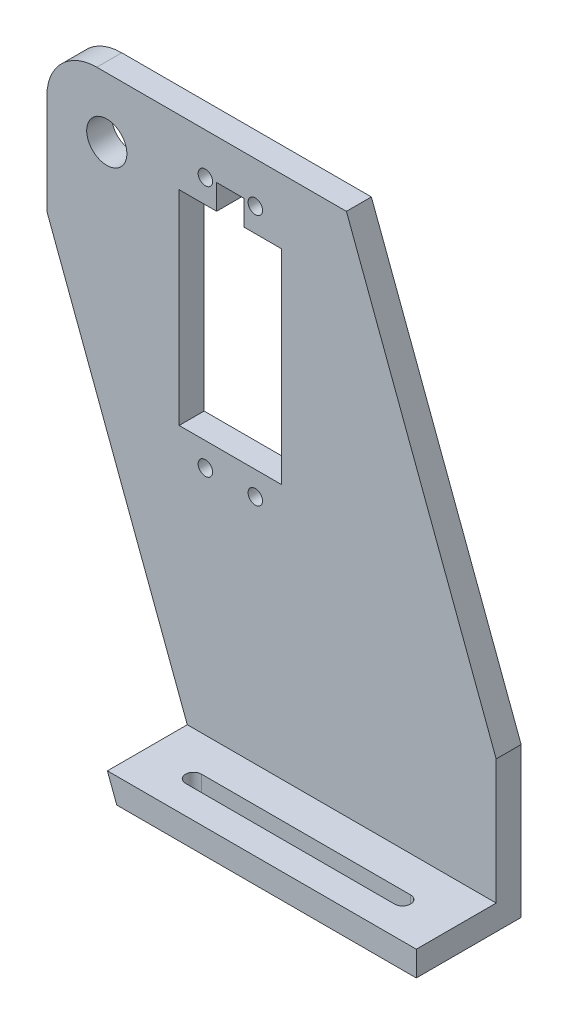
SolidWorks part; units mm, degrees
ref_plane "Front Plane" through (0, 0, 0) normal (0, 0, 1) x (1, 0, 0)
ref_plane "Top Plane" through (0, 0, 0) normal (0, 1, 0) x (1, 0, 0)
ref_plane "Right Plane" through (0, 0, 0) normal (1, 0, 0) x (0, 0, -1)
sketch "Sketch2" plane through (0, 0, 0) normal (0, 0, 1) x (1, 0, 0)
  line L1 (-45, 2.5) -> (45, 2.5)
  line L2 (-45, 2.5) -> (-45, -2.5)
  line L3 (-45, -2.5) -> (45, -2.5)
  line L4 (45, 2.5) -> (45, -2.5)
  line L5 (-45, 2.5) -> (45, -2.5) construction
  line L6 (-45, -2.5) -> (45, 2.5) construction
  point P0 (0, 0)
  dimension "D1" = 5
  dimension "D2" = 90
extrude "Boss-Extrude1" add sketch "Sketch2" along normal blind 21
sketch "Sketch3" plane through (0, 2.5, 0) normal (0, 1, 0) x (1, 0, 0)
  line L0 (45, -21) -> (45, 0) construction
  line L1 (-45, 0) -> (45, 0)
  line L2 (-45, 0) -> (-45, -5)
  line L3 (-45, -5) -> (45, -5)
  line L4 (45, 0) -> (45, -5)
  dimension "D1" = 5
extrude "Boss-Extrude2" add sketch "Sketch3" along normal blind 105
fillet "Fillet1" radius 10 1 edges at (-45, 107.5, 2.5)
sketch "Sketch4" plane through (0, 0, 5) normal (0, 0, 1) x (1, 0, 0)
  line L0 (-35, 107.5) -> (45, 107.5) construction
  line L1 (-45, 97.5) -> (-45, 2.5) construction
  circle A0 centre (-33, 95.5) radius 4.025
  dimension "D1" = 8.05
  dimension "D2" = 12
  dimension "D3" = 12
extrude "Cut-Extrude1" cut sketch "Sketch4" against normal through all
sketch "Sketch5" plane through (0, 0, 21) normal (0, 0, 1) x (1, 0, 0)
  line L0 (-45, 77.5) -> (-15, -2.5)
  line L1 (-45, 97.5) -> (-45, 2.5) construction
  line L2 (-45, -2.5) -> (45, -2.5) construction
  line L3 (-15, -2.5) -> (-45, -2.5)
  line L4 (-45, -2.5) -> (-45, 77.5)
  line L5 (15, 107.5) -> (45, 27.5)
  line L6 (-35, 107.5) -> (45, 107.5) construction
  line L7 (45, 107.5) -> (45, 2.5) construction
  line L8 (45, 27.5) -> (45, 107.5)
  line L9 (45, 107.5) -> (15, 107.5)
  dimension "D1" = 80
  dimension "D2" = 30
  dimension "D3" = 30
extrude "Cut-Extrude2" cut sketch "Sketch5" against normal through all
sketch "Sketch7" plane through (0, 0, 5) normal (0, 0, 1) x (1, 0, 0)
  circle A0 centre (-13.25, 48.85) radius 1.45
  circle A1 centre (-3.25, 48.85) radius 1.45
  circle A2 centre (-3.25, 99.25) radius 1.45
  circle A3 centre (-13.25, 99.25) radius 1.45
  dimension "D1" = 2.9
extrude "Cut-Extrude4" cut sketch "Sketch7" against normal blind 5
sketch "Sketch6" plane through (0, 0, 5) normal (0, 0, 1) x (1, 0, 0)
  line L0 (-18.5, 94.5) -> (2, 94.5)
  line L2 (-18.5, 94.5) -> (-18.5, 53.6)
  line L3 (-18.5, 53.6) -> (2, 53.6)
  line L4 (2, 94.5) -> (2, 53.6)
  line L9 (-35, 107.5) -> (15, 107.5) construction
  line L10 (-5.5, 94.5) -> (-5.5, 99.5)
  line L11 (-5.5, 99.5) -> (-11, 99.5)
  line L12 (-11, 99.5) -> (-11, 94.5)
  line L13 (-11, 94.5) -> (-5.5, 94.5)
  point P15 (-8.25, 94.5)
  point P16 (-8.25, 94.5)
  dimension "D1" = 20.5
  dimension "D2" = 40.9
  dimension "D3" = 5.5
  dimension "D4" = 5
  dimension "D5" = 13
  dimension "D6" = 13
extrude "Cut-Extrude3" cut sketch "Sketch6" against normal through all contours L11 L12 L0 L10 | L4 L0 L2 L3
sketch "Sketch8" plane through (0, 2.5, 0) normal (0, 1, 0) x (1, 0, 0)
  line L0 (-6.875, -13.75) -> (35, -13.75) construction
  line L1 (-6.875, -12.15) -> (35, -12.15)
  line L2 (-6.875, -15.35) -> (35, -15.35)
  line L3 (45, -21) -> (-16.875, -21) construction
  line L4 (45, -21) -> (45, -5) construction
  line L5 (-16.875, -5) -> (-16.875, -21) construction
  arc A0 (-6.875, -12.15) -> (-6.875, -15.35) centre (-6.875, -13.75) ccw
  arc A1 (35, -15.35) -> (35, -12.15) centre (35, -13.75) ccw
  point P2 (14.0625, -13.75)
  dimension "D1" = 1.6
  dimension "D2" = 7.25
  dimension "D3" = 10
  dimension "D4" = 10
extrude "Cut-Extrude5" cut sketch "Sketch8" against normal blind 10
